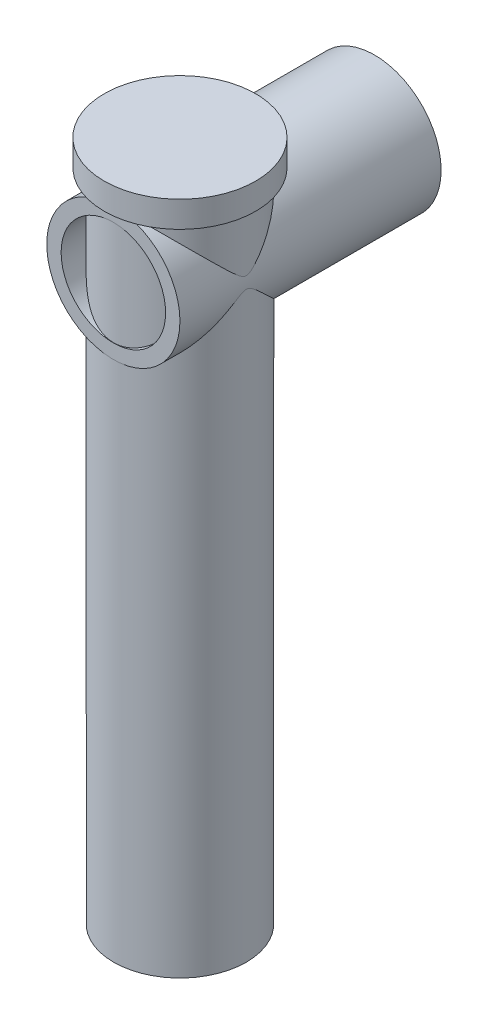
SolidWorks part; units mm, degrees
ref_plane "Alzado" through (0, 0, 0) normal (0, 0, 1) x (1, 0, 0)
ref_plane "Planta" through (0, 0, 0) normal (0, 1, 0) x (1, 0, 0)
ref_plane "Vista lateral" through (0, 0, 0) normal (1, 0, 0) x (0, 0, -1)
sketch "Croquis1" plane through (0, 0, 0) normal (0, 0, 1) x (1, 0, 0)
  circle A0 centre (0, 0) radius 12.75
  circle A1 centre (0, 0) radius 10
extrude "Saliente-Extruir1" add sketch "Croquis1" along normal blind 50
ref_plane "Plano1" through (0, -12.7, 0) normal (0, 1, 0) x (1, 0, 0)
sketch "Croquis2" plane through (0, -12.7, 0) normal (0, 1, 0) x (1, 0, 0)
  circle A0 centre (0, -37.25) radius 12.7
extrude "Saliente-Extruir2" add sketch "Croquis2" against normal blind 100 and the other way blind 25.4
sketch "Croquis3" plane through (0, -12.7, 0) normal (0, 1, 0) x (1, 0, 0)
  circle A0 centre (0, -37.25) radius 10
extrude "Cortar-Extruir1" cut sketch "Croquis3" along normal through all both and the other way through all
sketch "Croquis4" plane through (0, 0, 0) normal (0, 0, 1) x (1, 0, 0)
  circle A0 centre (0, 0) radius 10
extrude "Cortar-Extruir2" cut sketch "Croquis4" along normal blind 42
ref_plane "Plano2" through (0, 12.7, 0) normal (0, 1, 0) x (1, 0, 0)
sketch "Croquis5" plane through (0, 12.7, 0) normal (0, 1, 0) x (1, 0, 0)
  circle A0 centre (0, -37.25) radius 14.5
extrude "Saliente-Extruir4" add sketch "Croquis5" along normal blind 5 separate body
